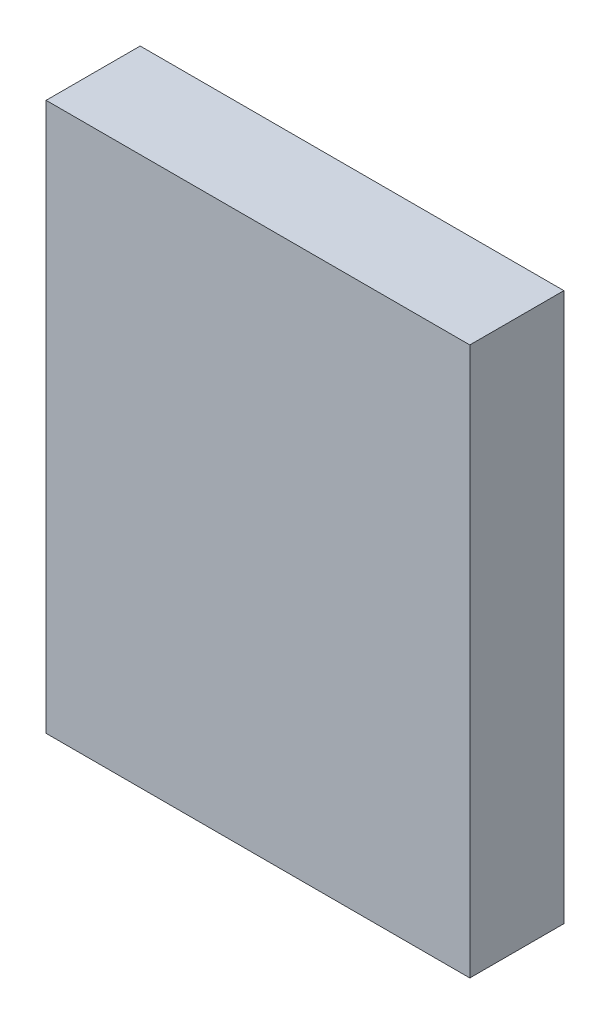
SolidWorks part; units mm, degrees
ref_plane "Front Plane" through (0, 0, 0) normal (0, 0, 1) x (1, 0, 0)
ref_plane "Top Plane" through (0, 0, 0) normal (0, 1, 0) x (1, 0, 0)
ref_plane "Right Plane" through (0, 0, 0) normal (1, 0, 0) x (0, 0, -1)
sketch "Sketch1" plane through (0, 0, 0) normal (0, 0, 1) x (1, 0, 0)
  line L0 (-0.5804, 6.1372) -> (4.4196, 6.1372)
  line L1 (4.4196, 6.1372) -> (4.4196, -0.3324)
  line L2 (4.4196, -0.3324) -> (-0.5804, -0.3324)
  line L3 (-0.5804, -0.3324) -> (-0.5804, 6.1372)
extrude "Component_Outline" add sketch "Sketch1" along normal blind 1.11 separate body
sketch3d "3DSketch1"
  line L0 (0, 0, 0) -> (1, 0, 0)
  line L1 (0, 0, 0) -> (0, 1, 0)
  line L2 (0, 0, 0) -> (0, 0, 1)
  point P0 (0, 0, 0)
